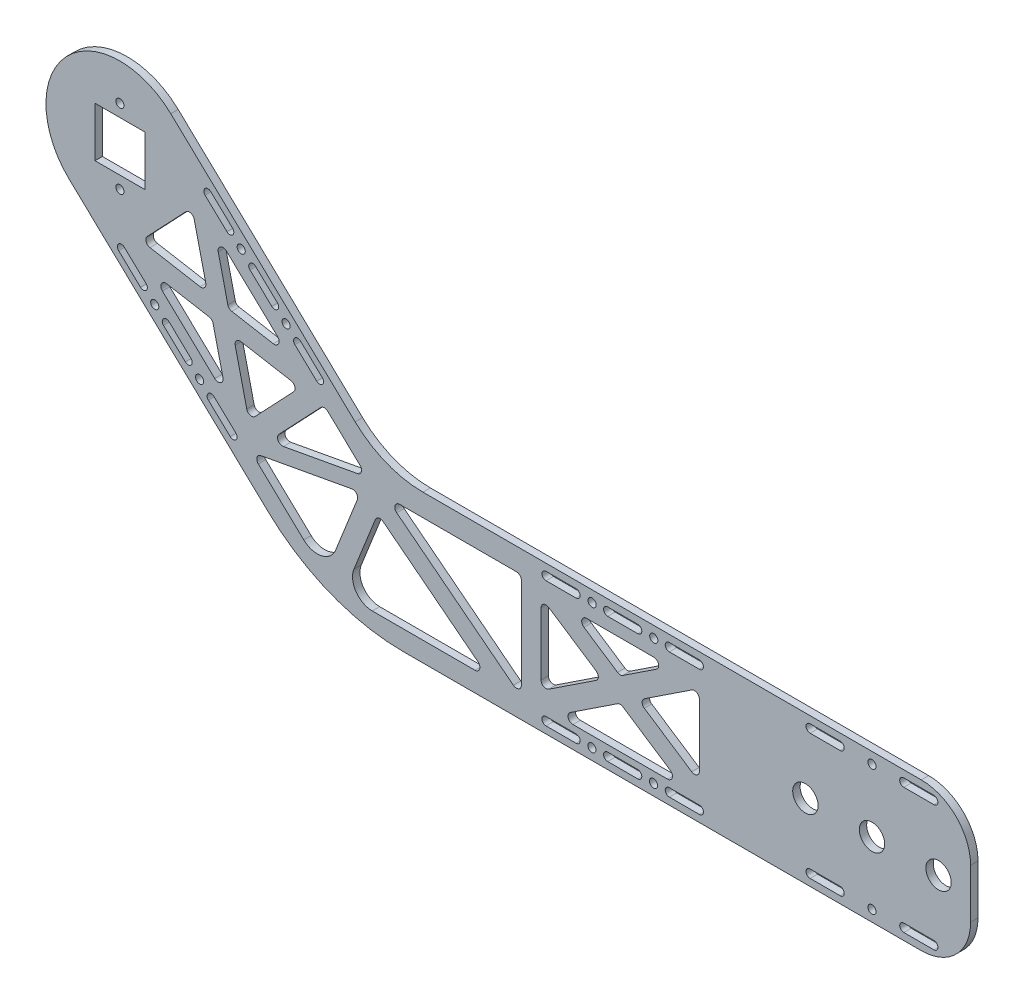
SolidWorks part; units mm, degrees
material "Thornel Mat VMA"
ref_plane "前视基准面" through (0, 0, 0) normal (0, 0, 1) x (1, 0, 0)
ref_plane "上视基准面" through (0, 0, 0) normal (0, 1, 0) x (1, 0, 0)
ref_plane "右视基准面" through (0, 0, 0) normal (1, 0, 0) x (0, 0, -1)
sketch "草图1" plane through (0, 0, 0) normal (0, 0, 1) x (1, 0, 0)
  line L0 (0, 0) -> (95, -90) construction
  line L1 (95, -90) -> (345, -90) construction
  line L2 (-20.6323, -21.7786) -> (83.0458, -120)
  line L3 (83.0458, -120) -> (345, -120)
  line L4 (20.6323, 21.7786) -> (106.9542, -60)
  line L5 (106.9542, -60) -> (345, -60)
  line L6 (345, -60) -> (345, -120)
  circle A1 centre (0, 0) radius 7.65
  circle A2 centre (0, 0) radius 30
  dimension "D6" = 15.3
  dimension "D1" = 250
  dimension "D2" = 345
  dimension "D3" = 90
  dimension "D4" = 30
  dimension "D5" = 30
extrude "凸台-拉伸1" add sketch "草图1" along normal blind 3
sketch "草图2" plane through (0, 0, 3) normal (0, 0, 1) x (1, 0, 0)
  line L0 (345, -90) -> (114.5407, -90) construction
  line L1 (345, -60) -> (345, -120) construction
  circle A0 centre (305, -90) radius 5.15
  circle A1 centre (278, -90) radius 5.15
  circle A2 centre (332, -90) radius 5.15
  dimension "D1" = 305
  dimension "D2" = 10.3
  dimension "D3" = 27
  dimension "D4" = 27
extrude "切除-拉伸1" cut sketch "草图2" against normal through all
sketch "草图3" plane through (0, 0, 3) normal (0, 0, 1) x (1, 0, 0)
  line L0 (345, -64.5) -> (105.161, -64.5) construction
  line L1 (345, -60) -> (345, -120) construction
  line L2 (345, -115.5) -> (84.839, -115.5) construction
  line L3 (106.9542, -60) -> (345, -60) construction
  line L4 (83.0458, -120) -> (345, -120) construction
  line L5 (222.8, -115.5) -> (235, -115.5) construction
  line L6 (222.8, -113.85) -> (235, -113.85)
  line L7 (222.8, -117.15) -> (235, -117.15)
  line L8 (345, -90) -> (113.6838, -90) construction
  line L9 (222.8, -64.5) -> (235, -64.5) construction
  line L10 (222.8, -66.15) -> (235, -66.15)
  line L11 (222.8, -62.85) -> (235, -62.85)
  line L12 (35.6863, 1.3182) -> (44.5429, -7.0723) construction
  line L13 (36.8211, 2.516) -> (45.6777, -5.8745)
  line L14 (34.5515, 0.1204) -> (43.4081, -8.2701)
  line L15 (0.6594, -35.6546) -> (104.3375, -133.876) construction
  line L16 (18.8082, -52.8482) -> (27.6648, -61.2387) construction
  line L17 (19.943, -51.6504) -> (28.7996, -60.0408)
  line L18 (-17.5375, -18.5118) -> (86.1407, -116.7332)
  line L19 (-17.5375, -18.5118) -> (86.1407, -116.7332) construction
  line L20 (197.8, -115.5) -> (210, -115.5) construction
  line L21 (17.5375, 18.5118) -> (103.8593, -63.2668)
  line L22 (17.5375, 18.5118) -> (103.8593, -63.2668) construction
  line L23 (197.8, -113.85) -> (210, -113.85)
  line L24 (197.8, -117.15) -> (210, -117.15)
  line L25 (197.8, -64.5) -> (210, -64.5) construction
  line L26 (197.8, -66.15) -> (210, -66.15)
  line L27 (197.8, -62.85) -> (210, -62.85)
  line L28 (172.8, -115.5) -> (185, -115.5) construction
  line L29 (172.8, -113.85) -> (185, -113.85)
  line L30 (172.8, -117.15) -> (185, -117.15)
  line L31 (172.8, -64.5) -> (185, -64.5) construction
  line L32 (172.8, -66.15) -> (185, -66.15)
  line L33 (172.8, -62.85) -> (185, -62.85)
  line L34 (17.6734, -54.046) -> (26.53, -62.4365)
  line L37 (0.6113, -35.7054) -> (9.468, -44.0959) construction
  line L38 (1.7461, -34.5076) -> (10.6027, -42.8981)
  line L39 (-0.5235, -36.9032) -> (8.3332, -45.2937)
  line L40 (53.8832, -15.8246) -> (62.7398, -24.2151) construction
  line L41 (55.0179, -14.6268) -> (63.8746, -23.0173)
  line L42 (52.7484, -17.0224) -> (61.605, -25.4129)
  line L43 (18.8562, -52.7973) -> (122.5344, -151.0187) construction
  line L44 (37.005, -69.9909) -> (45.8617, -78.3814) construction
  line L45 (38.1398, -68.7931) -> (46.9964, -77.1836)
  line L46 (35.8703, -71.1888) -> (44.7269, -79.5792)
  line L47 (72.08, -32.9674) -> (80.9366, -41.3578) construction
  line L48 (73.2148, -31.7695) -> (82.0714, -40.16)
  line L49 (70.9452, -34.1652) -> (79.8019, -42.5557)
  line L50 (330.1, -64.5) -> (317.9, -64.5) construction
  line L51 (330.1, -66.15) -> (317.9, -66.15)
  line L52 (330.1, -62.85) -> (317.9, -62.85)
  line L53 (330.1, -115.5) -> (317.9, -115.5) construction
  line L54 (330.1, -113.85) -> (317.9, -113.85)
  line L55 (330.1, -117.15) -> (317.9, -117.15)
  line L56 (279.9, -64.5) -> (292.1, -64.5) construction
  line L57 (279.9, -62.85) -> (292.1, -62.85)
  line L58 (279.9, -66.15) -> (292.1, -66.15)
  line L59 (279.9, -115.5) -> (292.1, -115.5) construction
  line L60 (279.9, -113.85) -> (292.1, -113.85)
  line L61 (279.9, -117.15) -> (292.1, -117.15)
  arc A0 (222.8, -113.85) -> (222.8, -117.15) centre (222.8, -115.5) ccw
  arc A1 (235, -117.15) -> (235, -113.85) centre (235, -115.5) ccw
  arc A2 (222.8, -66.15) -> (222.8, -62.85) centre (222.8, -64.5) cw
  arc A3 (235, -62.85) -> (235, -66.15) centre (235, -64.5) cw
  circle A4 centre (216.4, -115.5) radius 1.65
  circle A5 centre (216.5, -64.5) radius 1.65
  circle A6 centre (191.5, -64.5) radius 1.65
  circle A7 centre (191.4, -115.5) radius 1.65
  arc A8 (197.8, -113.85) -> (197.8, -117.15) centre (197.8, -115.5) ccw
  arc A9 (210, -117.15) -> (210, -113.85) centre (210, -115.5) ccw
  arc A10 (197.8, -66.15) -> (197.8, -62.85) centre (197.8, -64.5) cw
  arc A11 (210, -62.85) -> (210, -66.15) centre (210, -64.5) cw
  arc A14 (172.8, -113.85) -> (172.8, -117.15) centre (172.8, -115.5) ccw
  arc A15 (185, -117.15) -> (185, -113.85) centre (185, -115.5) ccw
  arc A16 (172.8, -66.15) -> (172.8, -62.85) centre (172.8, -64.5) cw
  arc A17 (185, -62.85) -> (185, -66.15) centre (185, -64.5) cw
  circle A18 centre (166.4, -115.5) radius 1.65 [skipped]
  circle A19 centre (166.5, -64.5) radius 1.65 [skipped]
  arc A23 (1.7461, -34.5076) -> (-0.5235, -36.9032) centre (0.6113, -35.7054) ccw
  arc A24 (8.3332, -45.2937) -> (10.6027, -42.8981) centre (9.468, -44.0959) ccw
  circle A25 centre (14.114, -48.4975) radius 1.65
  arc A26 (36.8211, 2.516) -> (34.5515, 0.1204) centre (35.6863, 1.3182) ccw
  arc A27 (43.4081, -8.2701) -> (45.6777, -5.8745) centre (44.5429, -7.0723) ccw
  circle A28 centre (49.189, -11.4739) radius 1.65
  circle A29 centre (67.3859, -28.6166) radius 1.65
  circle A30 centre (32.3109, -65.6402) radius 1.65
  arc A31 (19.943, -51.6504) -> (17.6734, -54.046) centre (18.8082, -52.8482) ccw
  arc A32 (26.53, -62.4365) -> (28.7996, -60.0408) centre (27.6648, -61.2387) ccw
  arc A33 (55.0179, -14.6268) -> (52.7484, -17.0224) centre (53.8832, -15.8246) ccw
  arc A34 (61.605, -25.4129) -> (63.8746, -23.0173) centre (62.7398, -24.2151) ccw
  arc A37 (38.1398, -68.7931) -> (35.8703, -71.1888) centre (37.005, -69.9909) ccw
  arc A38 (44.7269, -79.5792) -> (46.9964, -77.1836) centre (45.8617, -78.3814) ccw
  arc A39 (73.2148, -31.7695) -> (70.9452, -34.1652) centre (72.08, -32.9674) ccw
  arc A40 (79.8019, -42.5557) -> (82.0714, -40.16) centre (80.9366, -41.3578) ccw
  circle A41 centre (85.5827, -45.7594) radius 1.65 [skipped]
  circle A42 centre (50.5078, -82.783) radius 1.65 [skipped]
  arc A43 (330.1, -66.15) -> (330.1, -62.85) centre (330.1, -64.5) ccw
  arc A44 (317.9, -62.85) -> (317.9, -66.15) centre (317.9, -64.5) ccw
  circle A45 centre (305, -64.5) radius 1.65
  arc A46 (330.1, -113.85) -> (330.1, -117.15) centre (330.1, -115.5) cw
  arc A47 (317.9, -117.15) -> (317.9, -113.85) centre (317.9, -115.5) cw
  circle A48 centre (305, -115.5) radius 1.65
  arc A49 (279.9, -62.85) -> (279.9, -66.15) centre (279.9, -64.5) ccw
  arc A50 (292.1, -66.15) -> (292.1, -62.85) centre (292.1, -64.5) ccw
  arc A51 (279.9, -113.85) -> (279.9, -117.15) centre (279.9, -115.5) ccw
  arc A52 (292.1, -117.15) -> (292.1, -113.85) centre (292.1, -115.5) ccw
  point P12 (228.9, -115.5)
  point P21 (228.9, -64.5)
  point P38 (203.9, -115.5)
  point P45 (203.9, -64.5)
  point P56 (178.9, -115.5)
  point P63 (178.9, -64.5)
  point P68 (40.1146, -2.8771)
  point P81 (5.0396, -39.9007)
  point P93 (58.3115, -20.0198)
  point P102 (23.2365, -57.0434)
  point P113 (76.5083, -37.1626)
  point P119 (324, -64.5)
  point P122 (41.4334, -74.1862)
  point P135 (324, -62.85)
  point P140 (324, -115.5)
  point P149 (286, -64.5)
  point P154 (286, -115.5)
  dimension "D8" = 6.4
  dimension "D9" = 3.3
  dimension "D10" = 3.3
  dimension "D11" = 6.3
  dimension "D14" = 3.3
  dimension "D16" = 3.3
  dimension "D18" = 6.4
  dimension "D22" = 3.3
  dimension "D23" = 6.4
  dimension "D27" = 3.3
  dimension "D29" = 3.3
  dimension "D30" = 12.9
  dimension "D35" = 25.8
  dimension "D1" = 4.5
  dimension "D2" = 4.5
  dimension "D3" = 12.2
  dimension "D4" = 110
  dimension "D5" = 3.3
  dimension "D13" = 12.8
  dimension "D15" = 12.2
  dimension "D17" = 25
  dimension "D19" = 25
  dimension "D20" = 12.2
  dimension "D21" = 3.3
  dimension "D25" = 12.8001
  dimension "D26" = 12.2
  dimension "D28" = 14.9
  dimension "D31" = 12.2
  dimension "D32" = 12.2
  dimension "D33" = 3.3
  dimension "D34" = 3.3
  dimension "D36" = 25.8
  dimension "D6" = 4.5
  dimension "D7" = 4.5
  dimension "D12" = 3
  dimension "D24" = 3
fillet "圆角1" radius 20 2 edges at (345, -120, 1.5) (345, -60, 1.5)
extrude "切除-拉伸2" cut sketch "草图3" against normal through all
fillet "圆角2" radius 40 1 edges at (106.9542, -60, 1.5)
fillet "圆角3" radius 80 1 edges at (83.0458, -120, 1.5)
sketch "草图4" plane through (0, 0, 3) normal (0, 0, 1) x (1, 0, 0)
  line L0 (167.8, -60) -> (238, -60) construction
  line L1 (167.8, -60) -> (167.8, -120) construction
  line L2 (167.8, -120) -> (238, -120) construction
  line L3 (238, -60) -> (238, -120) construction
  line L4 (170.8, -105.7525) -> (170.8, -72.9261)
  line L5 (167.8, -66.15) -> (238, -112.5287) construction
  line L6 (167.8, -112.5287) -> (238, -66.15) construction
  line L7 (107.6738, -69) -> (162.8, -69)
  line L8 (162.8, -69) -> (162.8, -112)
  line L9 (170.8, -72.9261) -> (195.6435, -89.3393)
  line L10 (195.6435, -89.3393) -> (170.8, -105.7525)
  line L11 (182.6247, -71.15) -> (202.9, -84.5452)
  line L12 (202.9, -84.5452) -> (223.1753, -71.15)
  line L13 (223.1753, -71.15) -> (182.6247, -71.15)
  line L14 (210.1565, -89.3393) -> (235, -72.9261)
  line L15 (235, -72.9261) -> (235, -105.7525)
  line L16 (235, -105.7525) -> (210.1565, -89.3393)
  line L17 (177.0626, -111.2034) -> (202.9, -94.1335)
  line L18 (202.9, -94.1335) -> (228.7374, -111.2034)
  line L19 (228.7374, -111.2034) -> (177.0626, -111.2034)
  line L20 (35.1514, 8.0237) -> (-6.1133, -35.5335) construction
  line L21 (35.9178, -1.174) -> (30.9218, 3.5591) construction
  line L22 (162.8, -112) -> (107.6738, -69)
  line L23 (104.5895, -76.7402) -> (149.7928, -112)
  line L24 (149.7928, -112) -> (90.5395, -112)
  line L25 (90.5395, -112) -> (104.5895, -76.7402)
  line L26 (83.1078, -109.0387) -> (97.6197, -72.6197)
  line L27 (97.6197, -72.6197) -> (53.2542, -80.7564)
  line L28 (53.2542, -80.7564) -> (83.1078, -109.0387)
  line L29 (60.2485, -73.3735) -> (82.8272, -49.5404)
  line L30 (82.8272, -49.5404) -> (100.2421, -66.0387)
  line L31 (100.2421, -66.0387) -> (60.2485, -73.3735)
  line L32 (122.8931, -20) -> (85.3103, -114.3172) construction
  line L33 (87.565, -41.6313) -> (46.3004, -85.1885) construction
  line L34 (77.0055, -39.9065) -> (83.4316, -45.9944) construction
  line L35 (44.3671, -74.6927) -> (50.6262, -80.6223) construction
  line L36 (4.1769, -36.8105) -> (-1.8837, -31.0689) construction
  line L37 (-1.8837, -31.0689) -> (83.4316, -45.9944) construction
  line L38 (83.4316, -45.9944) -> (30.9218, 3.5591) construction
  line L39 (30.9218, 3.5591) -> (50.6262, -80.6223) construction
  line L40 (8.5064, -28.8258) -> (35.4994, -33.5481)
  line L41 (35.4994, -33.5481) -> (29.2651, -6.9138)
  line L42 (29.2651, -6.9138) -> (8.5064, -28.8258)
  line L43 (12.415, -37.6311) -> (37.4815, -42.0164)
  line L44 (37.4815, -42.0164) -> (43.305, -66.8953)
  line L45 (43.305, -66.8953) -> (12.415, -37.6311)
  line L46 (38.3341, -10.5573) -> (44.0664, -35.0469)
  line L47 (44.0664, -35.0469) -> (68.7407, -39.3635)
  line L48 (68.7407, -39.3635) -> (38.3341, -10.5573)
  line L49 (46.0486, -43.5151) -> (73.0416, -48.2375)
  line L50 (73.0416, -48.2375) -> (52.2829, -70.1494)
  line L51 (52.2829, -70.1494) -> (46.0486, -43.5151)
  line L53 (20.6323, 21.7786) -> (95.3833, -49.0381) construction
  line L54 (-20.6323, -21.7786) -> (59.9041, -98.0762) construction
  line L55 (122.8931, -60) -> (325, -60) construction
  arc A0 (95.3833, -49.0381) -> (122.8931, -60) centre (122.8931, -20) ccw construction
  arc A1 (95.3833, -49.0381) -> (122.8931, -60) centre (122.8931, -20) ccw construction
  arc A2 (95.3833, -49.0381) -> (122.8931, -60) centre (122.8931, -20) ccw construction
  arc A4 (235, -66.15) -> (235, -62.85) centre (235, -64.5) ccw construction
  dimension "D13" = 3
  dimension "D1" = 8
  dimension "D2" = 8
  dimension "D3" = 6
  dimension "D4" = 6
  dimension "D5" = 5
  dimension "D6" = 8
  dimension "D7" = 6
  dimension "D8" = 8
  dimension "D9" = 8
  dimension "D10" = 8
  dimension "D11" = 6
  dimension "D12" = 6
extrude "切除-拉伸3" cut sketch "草图4" against normal through all
fillet "圆角4" radius 2 34 edges at (235, -105.7525, 1.5) (210.1565, -89.3393, 1.5) (223.1753, -71.15, 1.5) (235, -72.9261, 1.5) (202.9, -94.1335, 1.5) (182.6247, -71.15, 1.5) (177.0626, -111.2034, 1.5) (170.8, -105.7525, 1.5) (202.9, -84.5452, 1.5) (228.7374, -111.2034, 1.5) (195.6435, -89.3393, 1.5) (170.8, -72.9261, 1.5) (107.6738, -69, 1.5) (162.8, -69, 1.5) (162.8, -112, 1.5) (149.7928, -112, 1.5) (104.5895, -76.7402, 1.5) (53.2542, -80.7564, 1.5) (97.6197, -72.6197, 1.5) (100.2421, -66.0387, 1.5) (82.8272, -49.5404, 1.5) (60.2485, -73.3735, 1.5) (52.2829, -70.1494, 1.5) (73.0416, -48.2375, 1.5) (68.7407, -39.3635, 1.5) (46.0486, -43.5151, 1.5) (38.3341, -10.5573, 1.5) (12.415, -37.6311, 1.5) (43.305, -66.8953, 1.5) (35.4994, -33.5481, 1.5) (37.4815, -42.0164, 1.5) (44.0664, -35.0469, 1.5) (8.5064, -28.8258, 1.5) (29.2651, -6.9138, 1.5)
fillet "圆角5" radius 8 2 edges at (83.1078, -109.0387, 1.5) (90.5395, -112, 1.5)
sketch "草图5" plane through (0, 0, 3) normal (0, 0, 1) x (1, 0, 0)
  line L1 (-10.1, -10.1) -> (10.1, -10.1)
  line L2 (-10.1, -10.1) -> (-10.1, 10.1)
  line L3 (-10.1, 10.1) -> (10.1, 10.1)
  line L4 (10.1, -10.1) -> (10.1, 10.1)
  line L5 (-10.1, -10.1) -> (10.1, 10.1) construction
  line L6 (-10.1, 10.1) -> (10.1, -10.1) construction
  circle A0 centre (0, 15.1) radius 1.65
  circle A1 centre (0, -15.1) radius 1.65
  point P0 (0, 0)
  dimension "D2" = 5
  dimension "D3" = 5
  dimension "D4" = 3.3
  dimension "D5" = 3.3
  dimension "D1" = 20.2
extrude "切除-拉伸4" cut sketch "草图5" against normal through all
